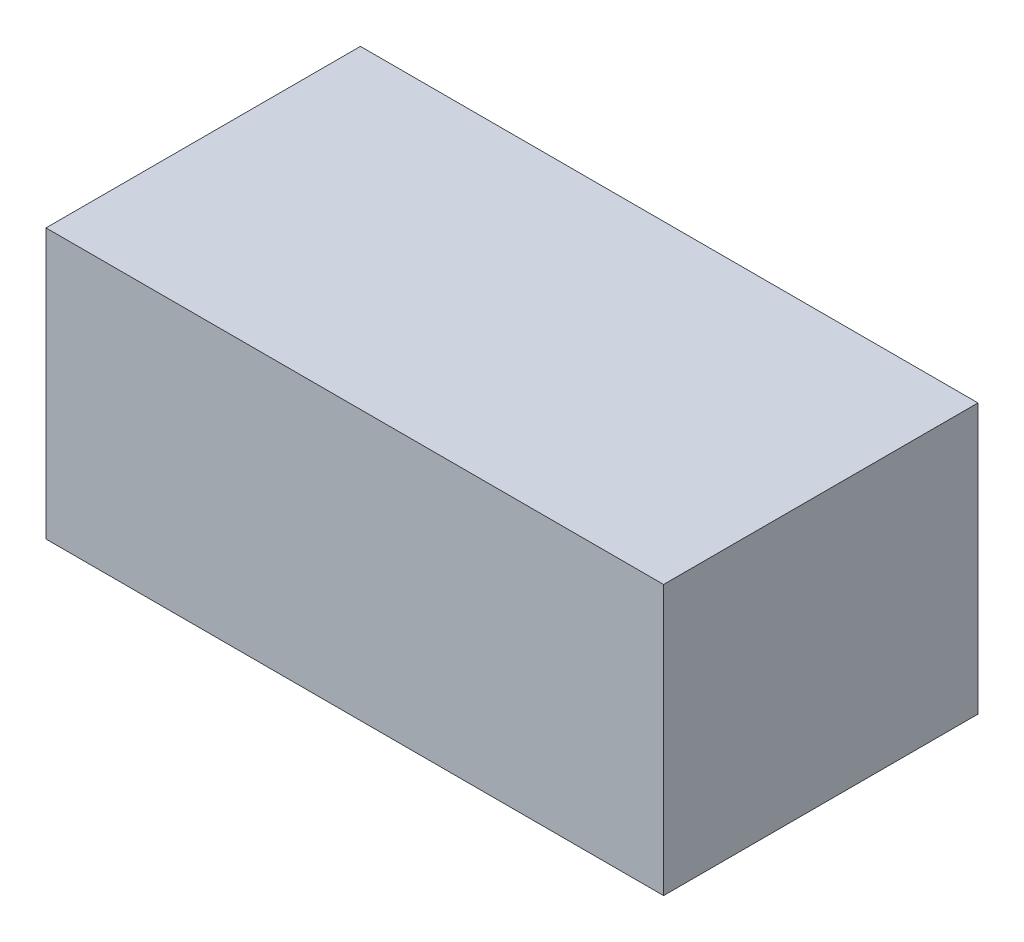
SolidWorks part; units mm, degrees
ref_plane "Front Plane" through (0, 0, 0) normal (0, 0, 1) x (1, 0, 0)
ref_plane "Top Plane" through (0, 0, 0) normal (0, 1, 0) x (1, 0, 0)
ref_plane "Right Plane" through (0, 0, 0) normal (1, 0, 0) x (0, 0, -1)
other "Configuration Table"
sketch "草图1" plane through (0, 0, 0) normal (0, 1, 0) x (1, 0, 0)
  line L1 (-27.5, -14) -> (27.5, -14)
  line L2 (-27.5, -14) -> (-27.5, 14)
  line L3 (-27.5, 14) -> (27.5, 14)
  line L4 (27.5, -14) -> (27.5, 14)
  line L5 (-27.5, -14) -> (27.5, 14) construction
  line L6 (-27.5, 14) -> (27.5, -14) construction
  point P0 (0, 0)
  dimension "D1" = 55
  dimension "D2" = 28
extrude "凸台-拉伸1" add sketch "草图1" along normal blind 24
